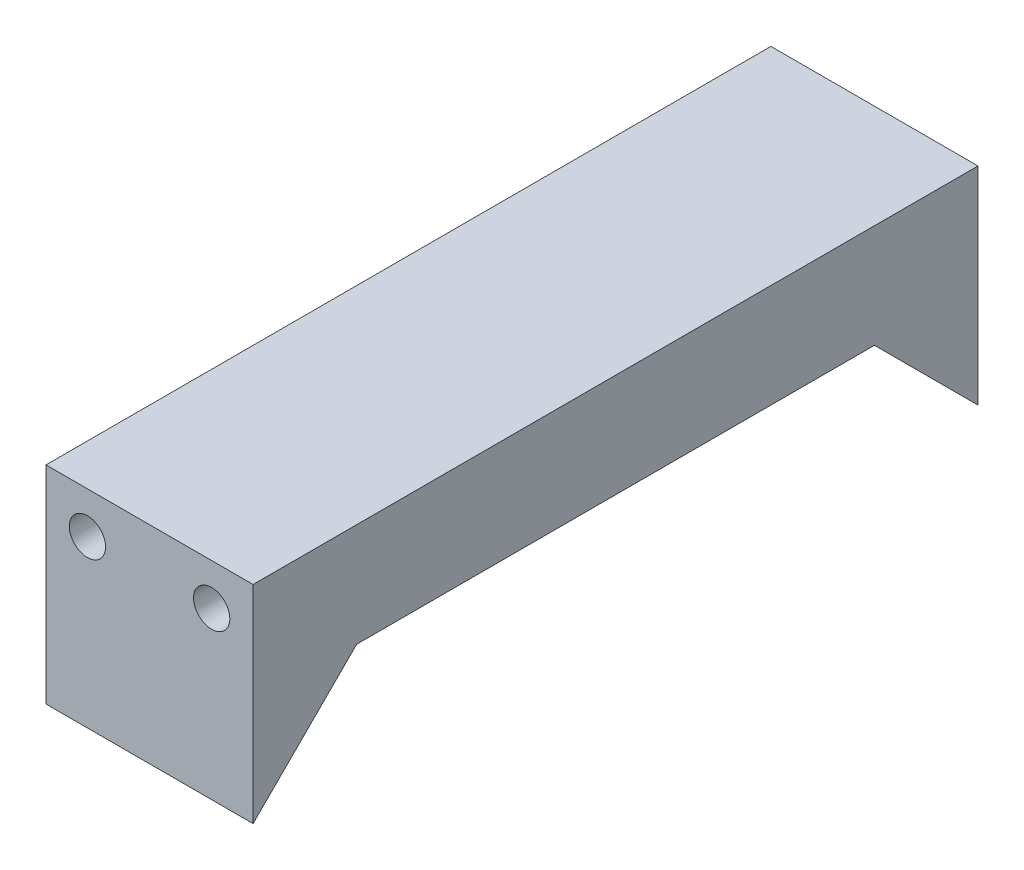
SolidWorks part; units mm, degrees
ref_plane "Front" through (0, 0, 0) normal (0, 0, 1) x (1, 0, 0)
ref_plane "Top" through (0, 0, 0) normal (0, 1, 0) x (1, 0, 0)
ref_plane "Right" through (0, 0, 0) normal (1, 0, 0) x (0, 0, -1)
sketch "Sketch1" plane through (0, 0, 0) normal (1, 0, 0) x (0, 0, -1)
  line L0 (70, 0) -> (60, 10)
  line L1 (0, 0) -> (70, 0)
  line L2 (0, 0) -> (0, 20)
  line L3 (0, 20) -> (70, 20)
  line L4 (70, 0) -> (70, 20)
  line L5 (0, 0) -> (10, 10)
  line L6 (60, 10) -> (10, 10)
  dimension "D1" = 20
  dimension "D2" = 70
  dimension "D3" = 45
  dimension "D4" = 45
  dimension "D5" = 10
  dimension "D6" = 10
extrude "Boss-Extrude1" add sketch "Sketch1" along normal blind 20 contours L6 L0 L4 L3 L2 L5
sketch "Sketch2" plane through (0, 0, -70) normal (0, 0, -1) x (-1, 0, 0)
  line L0 (0, 16) -> (-20, 16)
  line L1 (0, 0) -> (0, 20) construction
  line L2 (-20, 0) -> (-20, 20) construction
  line L3 (-20, 20) -> (0, 20) construction
  circle A0 centre (-4, 16) radius 1.75
  circle A1 centre (-16, 16) radius 1.75
  point P8 (-10, 20)
  dimension "D2" = 4
  dimension "D1" = 4
  dimension "D3" = 4
extrude "Cut-Extrude1" cut sketch "Sketch2" against normal through all contours A0 | A1
